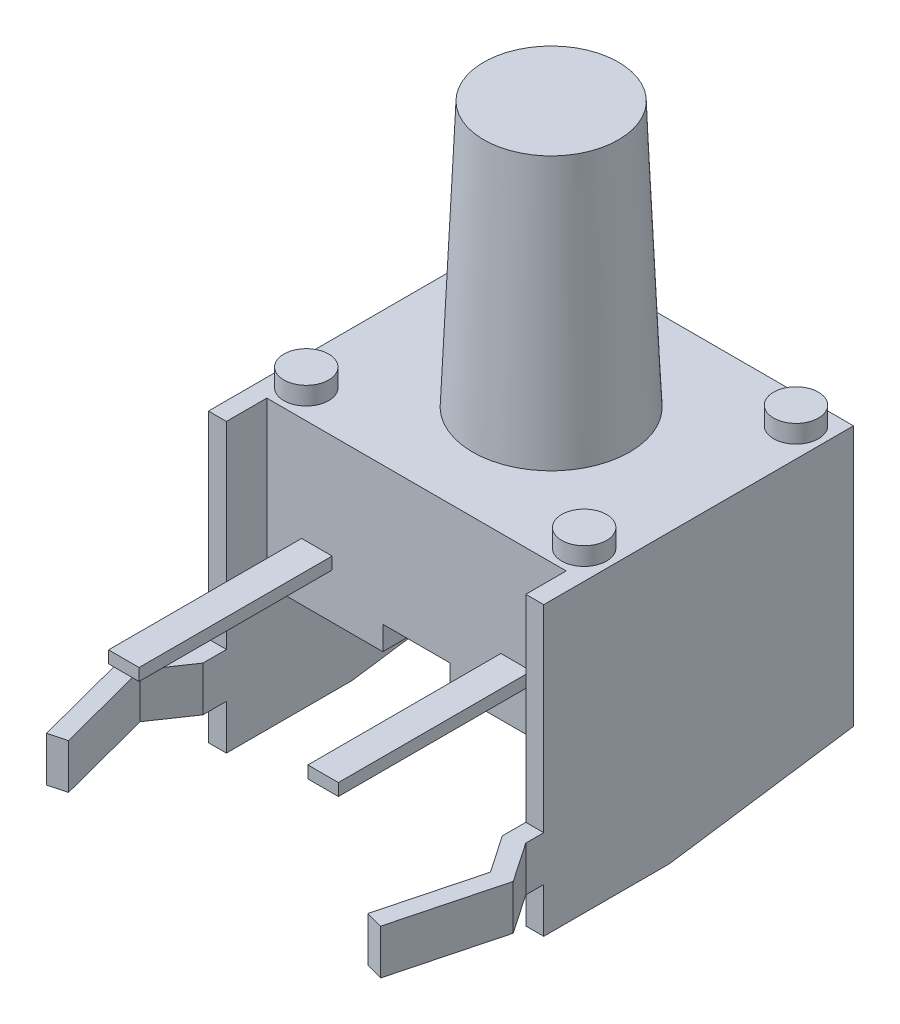
SolidWorks part; units mm, degrees
ref_plane "Front Plane" through (0, 0, 0) normal (0, 0, 1) x (1, 0, 0)
ref_plane "Top Plane" through (0, 0, 0) normal (0, 1, 0) x (1, 0, 0)
ref_plane "Right Plane" through (0, 0, 0) normal (1, 0, 0) x (0, 0, -1)
sketch "Sketch1" plane through (0, 0, 0) normal (0, 1, 0) x (1, 0, 0)
  line L1 (-3.5, -3) -> (3.5, -3)
  line L2 (-3.5, -3) -> (-3.5, 3)
  line L3 (-3.5, 3) -> (3.5, 3)
  line L4 (3.5, -3) -> (3.5, 3)
  line L5 (-3.5, -3) -> (3.5, 3) construction
  line L6 (-3.5, 3) -> (3.5, -3) construction
  point P0 (0, 0)
  dimension "D1" = 7
  dimension "D2" = 6
extrude "Boss-Extrude1" add sketch "Sketch1" along normal blind 5.05
sketch "Sketch3" plane through (0, 0, 3) normal (0, 0, 1) x (1, 0, 0)
  line L0 (0, 0) -> (0, 6.1897) construction
  line L1 (-3.5, 5.05) -> (3.5, 5.05) construction
  line L2 (-2.56, 2.46) -> (-1.88, 2.46)
  line L3 (1.88, 2.46) -> (2.56, 2.46)
  line L4 (1.88, 2.46) -> (1.88, 2.73)
  line L5 (1.88, 2.73) -> (2.56, 2.73)
  line L6 (2.56, 2.46) -> (2.56, 2.73)
  line L7 (1.88, 2.46) -> (2.56, 2.73) construction
  line L8 (1.88, 2.73) -> (2.56, 2.46) construction
  line L9 (-2.56, 2.46) -> (-2.56, 2.73)
  line L10 (-2.56, 2.73) -> (-1.88, 2.73)
  line L11 (-1.88, 2.46) -> (-1.88, 2.73)
  line L12 (-2.56, 2.46) -> (-1.88, 2.73) construction
  line L13 (-2.56, 2.73) -> (-1.88, 2.46) construction
  point P8 (2.22, 2.595)
  point P18 (-2.22, 2.595)
  dimension "D7" = 0.27
  dimension "D8" = 0.68
  dimension "D9" = 5.12
  dimension "D10" = 2.59
extrude "Boss-Extrude2" add sketch "Sketch3" along normal blind 4.3
sketch "Sketch4" plane through (0, 0, -3) normal (0, 0, -1) x (-1, 0, 0)
  line L0 (0, 0) -> (0, 3.4788) construction
  line L1 (-3.335, 5.05) -> (-3.735, 5.05)
  line L2 (-3.335, 5.05) -> (-3.335, -0.75)
  line L3 (-3.335, -0.75) -> (-3.735, -0.75)
  line L4 (-3.735, 5.05) -> (-3.735, -0.75)
  line L5 (3.735, 5.05) -> (3.335, 5.05)
  line L6 (3.735, 5.05) -> (3.735, -0.75)
  line L7 (3.735, -0.75) -> (3.335, -0.75)
  line L8 (3.335, 5.05) -> (3.335, -0.75)
  line L9 (-3.5, 5.05) -> (3.5, 5.05) construction
  dimension "D1" = 0.4
  dimension "D2" = 7.47
  dimension "D3" = 5.8
extrude "Boss-Extrude3" add sketch "Sketch4" against normal blind 6.9
sketch "Sketch6" plane through (0, 0, -3) normal (0, 0, -1) x (-1, 0, 0)
  line L0 (-3.735, 5.05) -> (3.735, 5.05) construction
  line L1 (-3.335, 0) -> (3.335, 0)
  line L2 (-3.335, 0) -> (-3.335, 1.45)
  line L3 (-3.335, 1.45) -> (3.335, 1.45)
  line L4 (3.335, 0) -> (3.335, 1.45)
  dimension "D1" = 3.6
extrude "Cut-Extrude1" cut sketch "Sketch6" against normal through all
sketch "Sketch7" plane through (0, 0, 3) normal (0, 0, 1) x (1, 0, 0)
  line L0 (-3.335, 1.45) -> (3.335, 1.45) construction
  line L1 (-0.75, 1.45) -> (0.75, 1.45)
  line L2 (-0.75, 1.45) -> (-0.75, 1.98)
  line L3 (-0.75, 1.98) -> (0.75, 1.98)
  line L4 (0.75, 1.45) -> (0.75, 1.98)
  line L5 (-3.335, 5.05) -> (3.335, 5.05) construction
  point P6 (0, 1.45)
  dimension "D1" = 1.5
  dimension "D2" = 3.07
extrude "Cut-Extrude2" cut sketch "Sketch7" against normal up to next
sketch "Sketch9" plane through (0, 5.05, 0) normal (0, 1, 0) x (1, 0, 0)
  line L0 (3.735, 3) -> (-3.735, 3) construction
  line L1 (-3.735, -3.9) -> (-3.735, 3) construction
  line L2 (0, 0) -> (0, 2.36) construction
  line L3 (0, 2.36) -> (0, 0) construction
  line L4 (0, 0) -> (2.999, 0) construction
  circle A0 centre (-3.095, 2.36) radius 0.5
  circle A1 centre (-3.095, -2.36) radius 0.5
  circle A2 centre (3.095, 2.36) radius 0.5
  circle A3 centre (3.095, -2.36) radius 0.5
  dimension "D1" = 1
  dimension "D2" = 0.64
  dimension "D3" = 0.64
extrude "Boss-Extrude5" add sketch "Sketch9" along normal blind 4 from surface at -3.6 starting at face at (-2.0425, 1.45, 0)
sketch "Sketch2" plane through (0, 0, 0) normal (0, 0, 1) x (1, 0, 0)
  line L0 (0, 5.05) -> (0, 10.95)
  line L1 (-3.335, 5.05) -> (3.335, 5.05) construction
  line L2 (0, 10.95) -> (1.5, 10.95)
  line L3 (1.5, 10.95) -> (1.75, 5.05)
  line L4 (1.75, 5.05) -> (0, 5.05)
  line L5 (0.75, 1.45) -> (3.335, 1.45) construction
  dimension "D1" = 1.75
  dimension "D2" = 1.5
  dimension "D3" = 9.5
revolve "Revolve1" add sketch "Sketch2" angle 360 about L0
sketch "Sketch10" plane through (-3.735, 0, 0) normal (-1, 0, 0) x (0, 0, 1)
  line L0 (3.9, -0.75) -> (3.9, -1.35)
  line L1 (3.9, -1.35) -> (1.1, -1.35)
  line L2 (1.1, -1.35) -> (-3, -0.75)
  line L3 (-3, -0.75) -> (3.9, -0.75)
  line L4 (3.9, 5.05) -> (-3, 5.05) construction
  dimension "D1" = 6.4
  dimension "D2" = 2.8
extrude "Boss-Extrude6" add sketch "Sketch10" against normal up to surface (0.4 mm away) up to face at (-3.335, 1.9167, 1.3)
sketch "Sketch8" plane through (0, -1.35, 0) normal (0, -1, 0) x (1, 0, 0)
  line L0 (-3.735, 3.9) -> (-3.735, 4.3)
  line L1 (-3.735, 4.3) -> (-4.335, 5.18)
  line L2 (-4.335, 5.18) -> (-3.7219, 7.52)
  line L3 (-3.7219, 7.52) -> (-3.335, 7.4186)
  line L4 (-3.335, 7.4186) -> (-3.9019, 5.2548)
  line L5 (-3.9019, 5.2548) -> (-3.335, 4.4234)
  line L6 (-3.335, 4.4234) -> (-3.335, 3.9)
  line L7 (-3.335, 3.9) -> (-3.735, 3.9)
  line L8 (-3.9019, 5.2548) -> (-4.2324, 5.0295) construction
  line L10 (-3.335, -3) -> (-3.735, -3) construction
  line L11 (-3.335, 3.9) -> (-3.735, 3.9) construction
  line L12 (-3.735, 1.1) -> (-3.735, 3.9) construction
  dimension "D1" = 1
  dimension "D2" = 1.28
  dimension "D3" = 10.52
  dimension "D4" = 0.4
extrude "Boss-Extrude4" add sketch "Sketch8" against normal blind 1 from offset 1 offset against normal yes
mirror "Mirror1" about plane through (0, 0, 0) normal (1, 0, 0) of "Boss-Extrude6", "Boss-Extrude4"
ref_plane "Button Pressed Limit" through (0, 10.65, 0) normal (0, -1, 0) x (-1, 0, 0)
